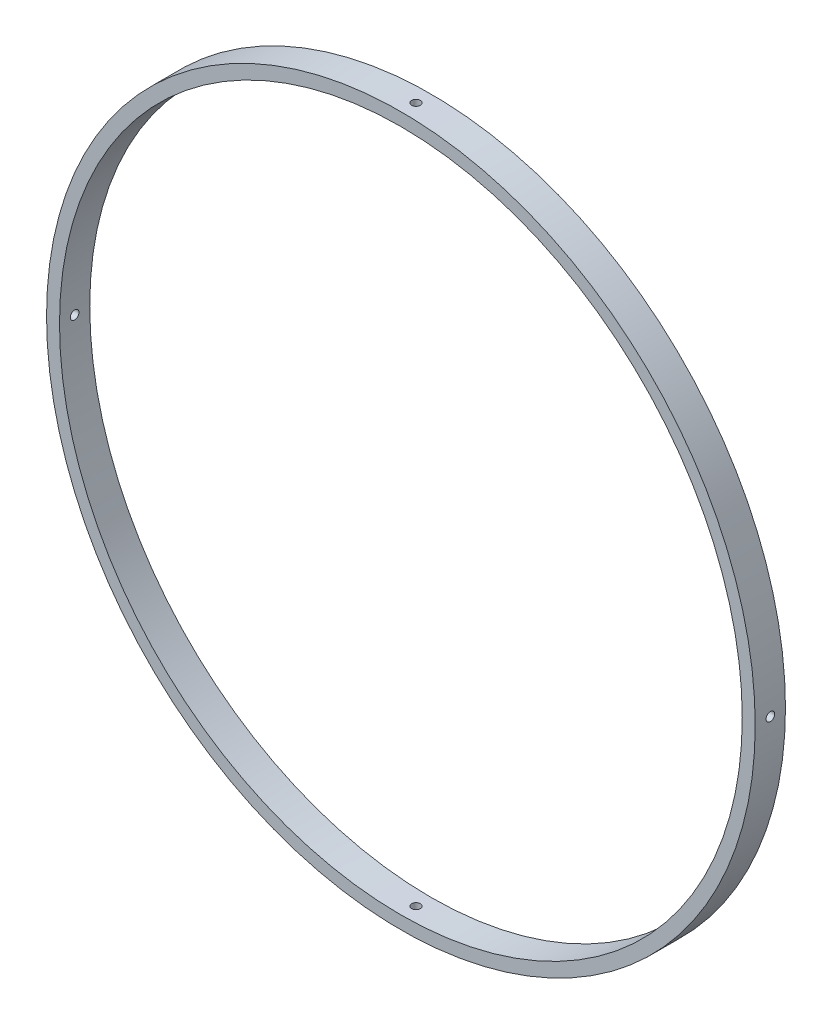
SolidWorks part; units mm, degrees
ref_plane "Front Plane" through (0, 0, 0) normal (0, 0, 1) x (1, 0, 0)
ref_plane "Top Plane" through (0, 0, 0) normal (0, 1, 0) x (1, 0, 0)
ref_plane "Right Plane" through (0, 0, 0) normal (1, 0, 0) x (0, 0, -1)
sketch "Sketch1" plane through (0, 0, 0) normal (0, 0, 1) x (1, 0, 0)
  circle A0 centre (0, 0) radius 82
  circle A1 centre (0, 0) radius 79
  dimension "D1" = 164
  dimension "D2" = 3
extrude "Boss-Extrude1" add sketch "Sketch1" along normal blind 7
sketch "Sketch2" plane through (0, 0, 0) normal (0, 1, 0) x (1, 0, 0)
  line L0 (82, 0) -> (-82, 0) construction
  circle A0 centre (0, -3.5) radius 1
  dimension "D2" = 2
  dimension "D1" = 3.5
extrude "Cut-Extrude1" cut sketch "Sketch2" against normal blind 125
pattern_circular "CirPattern1" count 4 every 90 about axis through (0, 0, 0) along (0, 0, 1) of "Cut-Extrude1"
